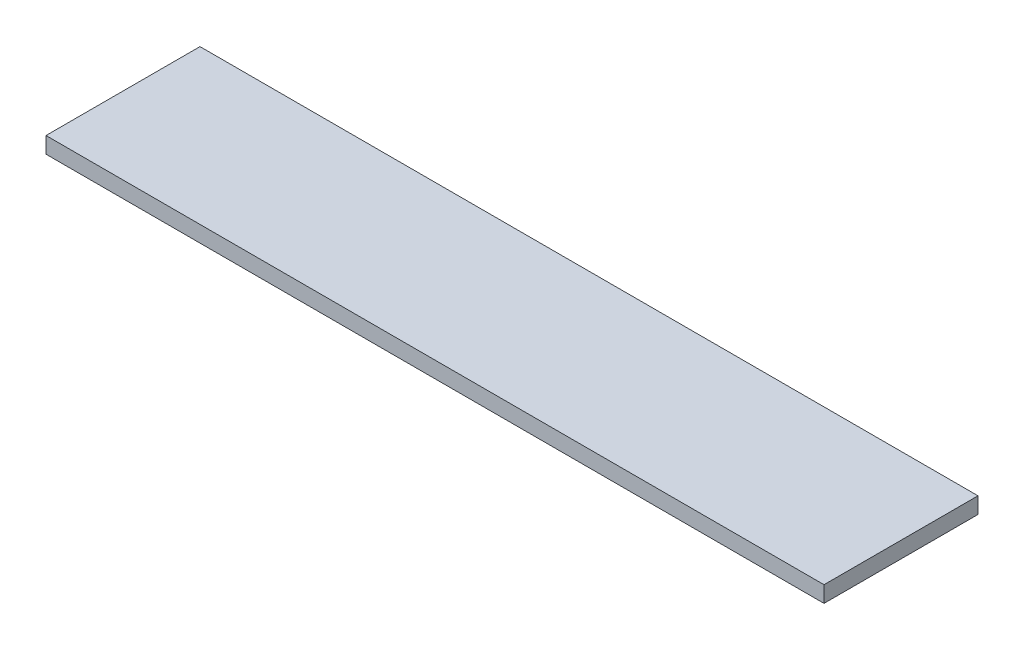
SolidWorks part; units mm, degrees
ref_plane "Front Plane" through (0, 0, 0) normal (0, 0, 1) x (1, 0, 0)
ref_plane "Top Plane" through (0, 0, 0) normal (0, 1, 0) x (1, 0, 0)
ref_plane "Right Plane" through (0, 0, 0) normal (1, 0, 0) x (0, 0, -1)
sketch "Sketch1" plane through (0, 0, 0) normal (0, 1, 0) x (1, 0, 0)
  line L0 (-314.325, 152.4) -> (-314.325, -12.7) construction
  line L1 (-304.8, 0) -> (304.8, 0)
  line L2 (-304.8, 0) -> (-304.8, 120.65)
  line L3 (-304.8, 120.65) -> (304.8, 120.65)
  line L4 (304.8, 0) -> (304.8, 120.65)
  line L5 (-304.8, 0) -> (304.8, 120.65) construction
  line L6 (-304.8, 120.65) -> (304.8, 0) construction
  line L7 (314.325, 152.4) -> (-144.4737, 152.4) construction
  dimension "D1" = 9.525
  dimension "D2" = 31.75
extrude "Boss-Extrude1" add sketch "Sketch1" along normal blind 12.7
